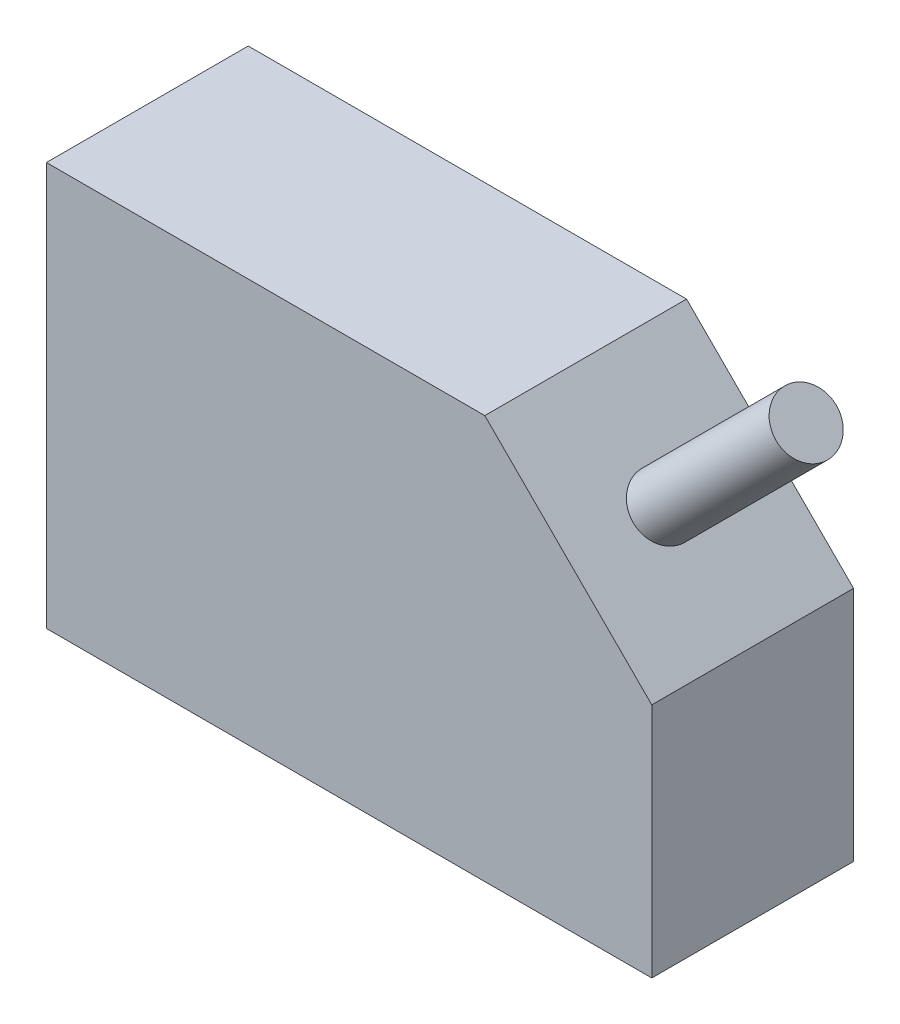
SolidWorks part; units mm, degrees
ref_plane "Front Plane" through (0, 0, 0) normal (0, 0, 1) x (1, 0, 0)
ref_plane "Top Plane" through (0, 0, 0) normal (0, 1, 0) x (1, 0, 0)
ref_plane "Right Plane" through (0, 0, 0) normal (1, 0, 0) x (0, 0, -1)
ref_plane "Plane1" through (0, 0, 0) normal (0, 0, -1) x (-1, 0, 0)
sketch "Sketch1" plane through (0, 0, 0) normal (0, 0, -1) x (-1, 0, 0)
  line L0 (-15, 1.724) -> (-15, -10)
  line L1 (-15, -10) -> (15, -10)
  line L2 (15, -10) -> (15, 10)
  line L3 (15, 10) -> (-6.724, 10)
  line L4 (-6.724, 10) -> (-15, 1.724)
extrude "Boss-Extrude1" add sketch "Sketch1" against normal blind 10
ref_plane "Plane2" through (0, 0, 5.2823) normal (0, 0, 1) x (1, 0, 0)
sketch "Sketch2" plane through (0, 0, 5.2823) normal (0, 0, 1) x (1, 0, 0)
  line L0 (18.9937, 11.8724) -> (17.9331, 12.9331)
  line L1 (17.9331, 12.9331) -> (10.862, 5.862)
  line L2 (10.862, 5.862) -> (11.9227, 4.8014)
  line L3 (11.9227, 4.8014) -> (18.9937, 11.8724)
  line L4 (18.4634, 13.4634) -> (10.3317, 5.3317) construction
revolve "Revolve1" add sketch "Sketch2" angle 360 about L4
